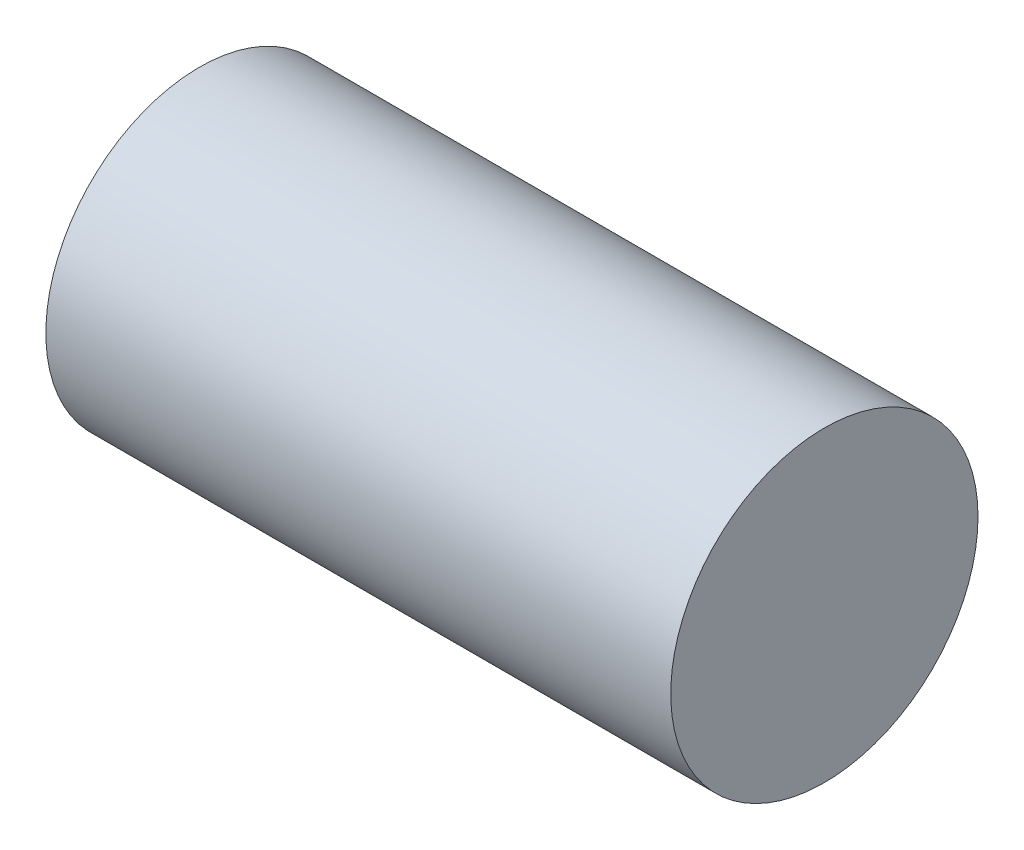
SolidWorks part; units mm, degrees
ref_plane "Front Plane" through (0, 0, 0) normal (0, 0, 1) x (1, 0, 0)
ref_plane "Top Plane" through (0, 0, 0) normal (0, 1, 0) x (1, 0, 0)
ref_plane "Right Plane" through (0, 0, 0) normal (1, 0, 0) x (0, 0, -1)
sketch "Sketch1" plane through (0, 0, 0) normal (1, 0, 0) x (0, 0, -1)
  circle A0 centre (0, 0) radius 2.95
  dimension "D1" = 5.9
extrude "Boss-Extrude1" add sketch "Sketch1" along normal blind 12
